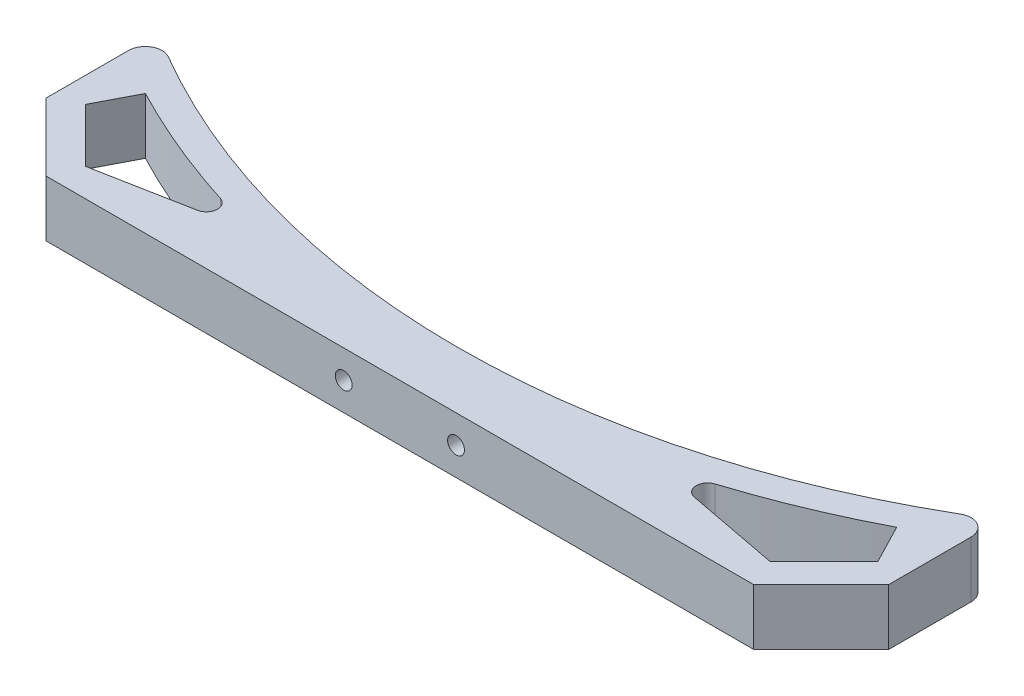
SolidWorks part; units mm, degrees
material "POM 乙缩醛共聚物"
ref_plane "前视基准面" through (0, 0, 0) normal (0, 0, 1) x (1, 0, 0)
ref_plane "上视基准面" through (0, 0, 0) normal (0, 1, 0) x (1, 0, 0)
ref_plane "右视基准面" through (0, 0, 0) normal (1, 0, 0) x (0, 0, -1)
sketch "草图1" plane through (0, 0, 0) normal (0, 1, 0) x (1, 0, 0)
  line L0 (0, 0) -> (0, -17.5) construction
  line L1 (-75, -17.5) -> (75, -17.5)
  line L2 (-75, -17.5) -> (-75, 17.5)
  line L4 (75, -17.5) -> (75, 17.5)
  line L5 (-75, -17.5) -> (75, 17.5) construction
  line L6 (-75, 17.5) -> (75, -17.5) construction
  arc A1 (-75, 17.5) -> (75, 17.5) centre (0, 135.7159) ccw
  point P0 (0, 0)
  dimension "D3" = 280
  dimension "D1" = 150
extrude "凸台-拉伸1" add sketch "草图1" along normal blind 10
chamfer "倒角1" distance 15 angle 45 2 edges at (-75, 5, 17.5) (75, 5, 17.5)
fillet "圆角1" radius 3 2 edges at (75, 5, -17.5) (-75, 5, -17.5)
sketch "草图2" plane through (0, 0, 0) normal (0, 0, 1) x (1, 0, 0)
  line L0 (75, 5) -> (-75, 5) construction
  line L2 (75, 0) -> (75, 10) construction
  line L3 (-75, 10) -> (-75, 0) construction
  circle A0 centre (10, 5) radius 1.5
  circle A1 centre (-10, 5) radius 1.5
  dimension "D1" = 3
  dimension "D2" = 3
  dimension "D3" = 20
  dimension "D4" = 10
extrude "切除-拉伸2" cut sketch "草图2" along normal through all
sketch "草图4" plane through (0, 0, 0) normal (0, 0, 1) x (1, 0, 0)
  circle A0 centre (10, 5) radius 3.5
  circle A1 centre (-10, 5) radius 3.5
  dimension "D1" = 7
  dimension "D2" = 7
extrude "切除-拉伸3" cut sketch "草图4" along normal blind 10
sketch "草图5" plane through (0, 0, 0) normal (0, -1, 0) x (1, 0, 0)
  line L0 (-60, 17.5) -> (-75, 2.5) construction
  line L1 (-60, 17.5) -> (-75, 2.5)
  line L2 (-60.9289, 9.5) -> (-70.5, -0.0711)
  line L3 (-56.4645, 13.9645) -> (-71.4645, -1.0355) construction
  line L4 (0, 4.2841) -> (0, 41.6421) construction
  line L5 (-70.5, -0.0711) -> (-66.8698, -7.0558)
  line L6 (-60.9289, 9.5) -> (-36, 4.7441)
  line L7 (60.9289, 9.5) -> (36, 4.7441)
  line L8 (60.9289, 9.5) -> (70.5, -0.0711)
  line L9 (70.5, -0.0711) -> (66.8698, -7.0558)
  line L10 (-75, -12.1643) -> (-75, 2.5) construction
  line L11 (-60, 17.5) -> (60, 17.5) construction
  arc A0 (-36, 4.7441) -> (-66.8698, -7.0558) centre (0, -135.7159) ccw
  arc A1 (70.4895, -14.7563) -> (-70.4895, -14.7563) centre (0, -135.7159) ccw construction
  arc A2 (36, 4.7441) -> (66.8698, -7.0558) centre (0, -135.7159) cw
  dimension "D1" = 290
  dimension "D3" = 36
  dimension "D4" = 4.5
  dimension "D5" = 8
  dimension "D2" = 5
extrude "切除-拉伸4" cut sketch "草图5" against normal through all contours A0 L6 L2 L5 | L7 A2 L9 L8
fillet "圆角2" radius 2 2 edges at (36, 5, 4.7441) (-36, 5, 4.7441)
sketch "草图6" plane through (0, 0, 0) normal (0, -1, 0) x (1, 0, 0)
  line L0 (-60, 17.5) -> (60, 17.5) construction
  line L1 (-75, 14.51) -> (75, 14.51)
  line L2 (-75, 14.51) -> (-75, 20.49)
  line L3 (-75, 20.49) -> (75, 20.49)
  line L4 (75, 14.51) -> (75, 20.49)
  line L5 (-75, 14.51) -> (75, 20.49) construction
  line L6 (-75, 20.49) -> (75, 14.51) construction
  point P0 (0, 17.5)
  dimension "D1" = 150
  dimension "D2" = 5.98
extrude "切除-拉伸5" cut sketch "草图6" against normal through all
